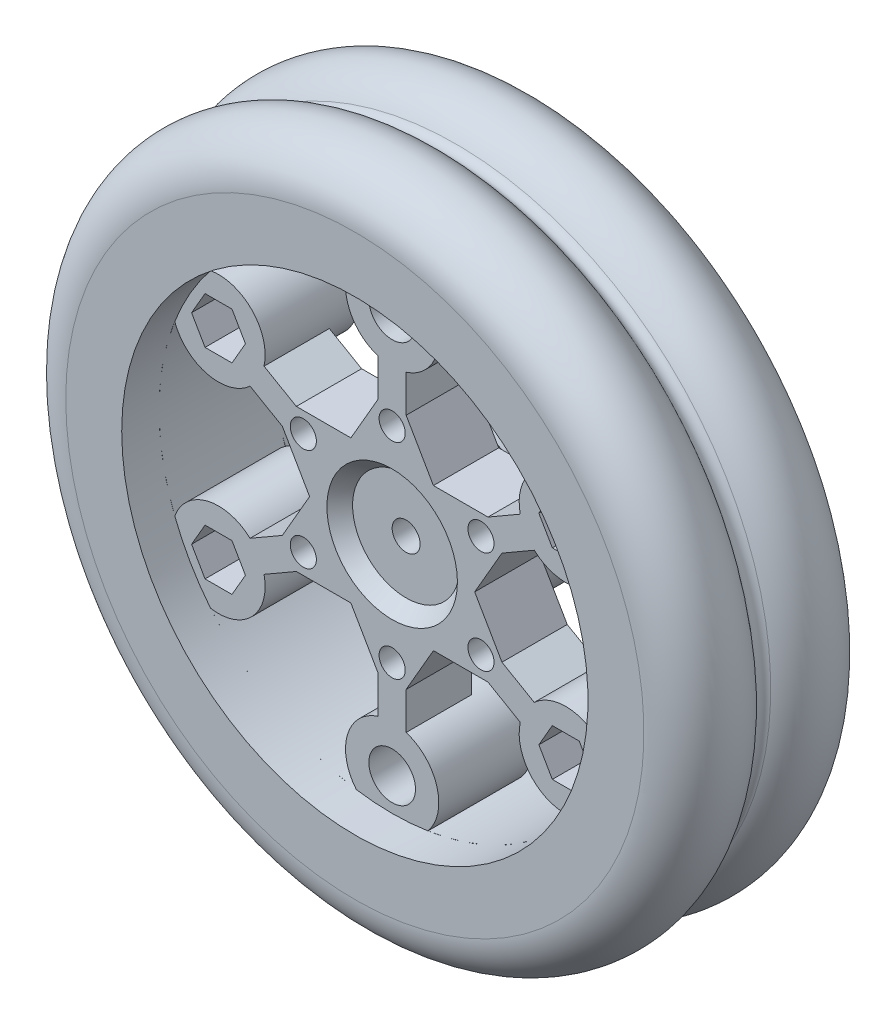
SolidWorks part; units mm, degrees
material "尼龙 6/10"
ref_plane "前视基准面" through (0, 0, 0) normal (0, 0, 1) x (1, 0, 0)
ref_plane "上视基准面" through (0, 0, 0) normal (0, 1, 0) x (1, 0, 0)
ref_plane "右视基准面" through (0, 0, 0) normal (1, 0, 0) x (0, 0, -1)
sketch "草图1" plane through (0, 0, 0) normal (0, 1, 0) x (1, 0, 0)
  line L0 (25, 10) -> (25, -10)
  line L1 (0, 146.934) -> (0, -105.6267) construction
  line L2 (25, 10) -> (31, 10)
  line L3 (25, -10) -> (31, -10)
  line L4 (-236.5493, 0) -> (326.6118, 0) construction
  arc A0 (33.7639, 0.8333) -> (31, 10) centre (31, 5) ccw
  arc A1 (33.7639, 0.8333) -> (33.7639, -0.8333) centre (34.3166, 0) ccw
  arc A2 (31, -10) -> (33.7639, -0.8333) centre (31, -5) ccw
  point P15 (31, 0)
  dimension "D4" = 1
  dimension "D1" = 20
  dimension "D2" = 25
  dimension "D3" = 31
revolve "旋转1" add sketch "草图1" angle 360 about L1
ref_plane "基准面1" through (0, 0, 6) normal (0, 0, 1) x (1, 0, 0)
sketch "草图2" plane through (0, 0, 6) normal (0, 0, 1) x (1, 0, 0)
  line L0 (0, 38.7462) -> (0, -39.0495) construction
  circle A0 centre (0, 0) radius 21.5 construction
  circle A1 centre (0, 21.5) radius 5
  dimension "D1" = 43
  dimension "D2" = 10
extrude "凸台-拉伸1" add sketch "草图2" against normal blind 10
pattern_circular "阵列(圆周)1" count 6 over 360 about axis through (0, 0, 0) along (0, 0, 1) of "凸台-拉伸1"
sketch "草图3" plane through (0, 0, 6) normal (0, 0, 1) x (1, 0, 0)
  line L0 (-8.8498, 0) -> (-11.7748, -5.0661)
  line L1 (0, 16) -> (-13.8564, 8) construction
  line L2 (-13.8564, 8) -> (-13.8564, -8) construction
  line L3 (-13.8564, -8) -> (0, -16) construction
  line L4 (0, -16) -> (13.8564, -8) construction
  line L5 (13.8564, -8) -> (13.8564, 8) construction
  line L6 (13.8564, 8) -> (0, 16) construction
  line L7 (-10.2748, -7.6642) -> (-4.4249, -7.6642)
  line L8 (11.7748, -5.0661) -> (8.8498, 0)
  line L9 (10.2748, 7.6642) -> (4.4249, 7.6642)
  line L10 (-11.7748, 5.0661) -> (-8.8498, 0)
  line L11 (-4.4249, -7.6642) -> (-1.5, -12.7303)
  line L12 (0, 43.2923) -> (0, -38.3052) construction
  line L13 (-1.5, 16.7303) -> (-1.5, 12.7303)
  line L14 (1.5, 12.7303) -> (1.5, 16.7303)
  line L15 (11.7748, 5.0661) -> (15.2389, 7.0661)
  line L16 (13.7389, 9.6642) -> (10.2748, 7.6642)
  line L17 (10.2748, -7.6642) -> (13.7389, -9.6642)
  line L18 (15.2389, -7.0661) -> (11.7748, -5.0661)
  line L19 (-1.5, -12.7303) -> (-1.5, -16.7303)
  line L20 (1.5, -16.7303) -> (1.5, -12.7303)
  line L21 (-11.7748, -5.0661) -> (-15.2389, -7.0661)
  line L22 (-13.7389, -9.6642) -> (-10.2748, -7.6642)
  line L23 (-10.2748, 7.6642) -> (-13.7389, 9.6642)
  line L24 (-15.2389, 7.0661) -> (-11.7748, 5.0661)
  line L25 (-1.5, 12.7303) -> (-4.4249, 7.6642)
  line L26 (1.5, -12.7303) -> (4.4249, -7.6642)
  line L27 (4.4249, -7.6642) -> (10.2748, -7.6642)
  line L28 (-4.4249, 7.6642) -> (-10.2748, 7.6642)
  line L29 (4.4249, 7.6642) -> (1.5, 12.7303)
  line L30 (8.8498, 0) -> (11.7748, 5.0661)
  circle A0 centre (0, 0) radius 13.8564 construction
  arc A1 (-3.839, 24.7035) -> (3.839, 24.7035) centre (0, 21.5) ccw construction
  arc A2 (-1.5, 16.7303) -> (1.5, 16.7303) centre (0, 21.5) ccw
  arc A3 (-23.3133, 9.0271) -> (-19.4744, 15.6764) centre (-18.6195, 10.75) ccw construction
  arc A4 (-19.4744, -15.6764) -> (-23.3133, -9.0271) centre (-18.6195, -10.75) ccw construction
  arc A5 (3.839, -24.7035) -> (-3.839, -24.7035) centre (0, -21.5) ccw construction
  arc A6 (23.3133, -9.0271) -> (19.4744, -15.6764) centre (18.6195, -10.75) ccw construction
  arc A7 (19.4744, 15.6764) -> (23.3133, 9.0271) centre (18.6195, 10.75) ccw construction
  arc A8 (-15.2389, 7.0661) -> (-13.7389, 9.6642) centre (-18.6195, 10.75) ccw
  arc A9 (-13.7389, -9.6642) -> (-15.2389, -7.0661) centre (-18.6195, -10.75) ccw
  arc A10 (1.5, -16.7303) -> (-1.5, -16.7303) centre (0, -21.5) ccw
  arc A11 (15.2389, -7.0661) -> (13.7389, -9.6642) centre (18.6195, -10.75) ccw
  arc A12 (13.7389, 9.6642) -> (15.2389, 7.0661) centre (18.6195, 10.75) ccw
  point P41 (0, 0)
  dimension "D1" = 32
  dimension "D2" = 3
  dimension "D3" = 6
extrude "凸台-拉伸2" add sketch "草图3" against normal blind 7
sketch "草图4" plane through (0, 0, -1) normal (0, 0, -1) x (-1, 0, 0)
  line L0 (0, 15.11) -> (0, -12.4392) construction
  circle A0 centre (0, 0) radius 11 construction
  circle A1 centre (0, 11) radius 1.4
  dimension "D1" = 22
  dimension "D2" = 2.8
extrude "切除-拉伸1" cut sketch "草图4" against normal through all
pattern_circular "阵列(圆周)2" count 6 over 360 about axis through (0, 0, 0) along (0, 0, 1) of "切除-拉伸1"
sketch "草图5" plane through (0, 0, -1) normal (0, 0, -1) x (-1, 0, 0)
  circle A0 centre (0, 0) radius 9
  dimension "D1" = 18
extrude "凸台-拉伸3" add sketch "草图5" along normal blind 5
sketch "草图7" plane through (0, 0, 6) normal (0, 0, 1) x (1, 0, 0)
  circle A0 centre (0, 0) radius 7
  dimension "D1" = 14
extrude "切除-拉伸3" cut sketch "草图7" against normal blind 1.5 draft 40
sketch "草图8" plane through (0, 0, 4.5) normal (0, 0, 1) x (1, 0, 0)
  circle A0 centre (0, 0) radius 1.5
  dimension "D1" = 3
extrude "切除-拉伸4" cut sketch "草图8" against normal through all
sketch "草图10" plane through (0, 0, 6) normal (0, 0, 1) x (1, 0, 0)
  circle A0 centre (0, 21.5) radius 1.25
  dimension "D1" = 2.5
extrude "切除-拉伸6" cut sketch "草图10" against normal through all
pattern_circular "阵列(圆周)3" count 6 over 360 about axis through (0, 0, 0) along (0, 0, 1) of "切除-拉伸6"
sketch "草图11" plane through (0, 0, 6) normal (0, 0, 1) x (1, 0, 0)
  circle A0 centre (0, 21.5) radius 2.5
  dimension "D1" = 5
extrude "切除-拉伸7" cut sketch "草图11" against normal through all
pattern_circular "阵列(圆周)4" count 2 over 360 about axis through (0, 0, 0) along (0, 0, 1) of "切除-拉伸7"
sketch "草图12" plane through (0, 0, 6) normal (0, 0, 1) x (1, 0, 0)
  line L1 (20.0629, 8.25) -> (21.5063, 10.75)
  line L2 (21.5063, 10.75) -> (20.0629, 13.25)
  line L3 (20.0629, 13.25) -> (17.1762, 13.25)
  line L4 (17.1762, 13.25) -> (15.7328, 10.75)
  line L5 (15.7328, 10.75) -> (17.1762, 8.25)
  line L6 (17.1762, 8.25) -> (20.0629, 8.25)
  circle A0 centre (18.6195, 10.75) radius 2.5 construction
  dimension "D1" = 5
extrude "切除-拉伸8" cut sketch "草图12" against normal blind 8
pattern_circular "阵列(圆周)5" count 6 over 360 about axis through (0, 0, 0) along (0, 0, 1) skipping 2, 5 of "切除-拉伸8"
sketch "草图13" plane through (0, 0, 0) normal (0, 1, 0) x (1, 0, 0)
  line L0 (0, 19.3352) -> (0, -18.3764) construction
  line L1 (21, 6) -> (26, 6)
  line L2 (26, 6) -> (26, -6)
  line L3 (26, -6) -> (21, -6)
  line L4 (-6.1819, 0) -> (35.4823, 0) construction
  dimension "D1" = 26
  dimension "D2" = 12
  dimension "D3" = 5
surface "曲面-旋转1" sketch "草图13" parameters "D1"=360
surface "曲面-剪裁2"
sketch "草图14" plane through (0, 0, -6) normal (0, 0, -1) x (-1, 0, 0)
  line L0 (0, 11) -> (0, 0) construction
  line L2 (0, 6.9282) -> (-6, 3.4641)
  line L3 (-6, 3.4641) -> (-6, -3.4641)
  line L4 (-6, -3.4641) -> (0, -6.9282)
  line L5 (0, -6.9282) -> (6, -3.4641)
  line L6 (6, -3.4641) -> (6, 3.4641)
  line L7 (6, 3.4641) -> (0, 6.9282)
  circle A0 centre (0, 0) radius 6 construction
  dimension "D1" = 12
extrude "切除-拉伸9" cut sketch "草图14" against normal blind 8
